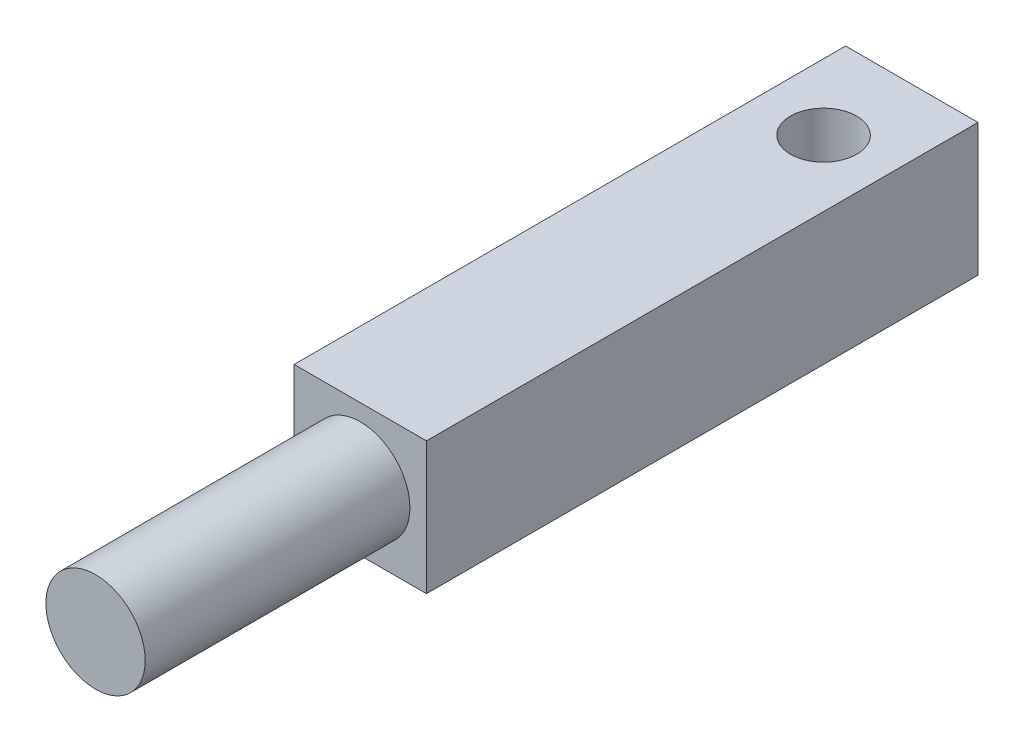
SolidWorks part; units mm, degrees
ref_plane "Alzado" through (0, 0, 0) normal (0, 0, 1) x (1, 0, 0)
ref_plane "Planta" through (0, 0, 0) normal (0, 1, 0) x (1, 0, 0)
ref_plane "Vista lateral" through (0, 0, 0) normal (1, 0, 0) x (0, 0, -1)
sketch "Croquis1" plane through (0, 0, 0) normal (0, 0, 1) x (1, 0, 0)
  line L1 (-6, -6) -> (6, -6)
  line L2 (-6, -6) -> (-6, 6)
  line L3 (-6, 6) -> (6, 6)
  line L4 (6, -6) -> (6, 6)
  line L5 (-6, -6) -> (6, 6) construction
  line L6 (-6, 6) -> (6, -6) construction
  point P0 (0, 0)
  dimension "D1" = 12
  dimension "D2" = 12
extrude "Saliente-Extruir1" add sketch "Croquis1" along normal blind 50
sketch "Croquis2" plane through (0, 0, 50) normal (0, 0, 1) x (1, 0, 0)
  line L0 (6, 6) -> (-6, -6) construction
  line L1 (-6, 6) -> (6, -6) construction
  circle A0 centre (0, 0) radius 4.5
  dimension "D1" = 9
extrude "Saliente-Extruir2" add sketch "Croquis2" along normal blind 24
sketch "Croquis3" plane through (0, 6, 0) normal (0, 1, 0) x (1, 0, 0)
  line L0 (-6, 0) -> (6, 0) construction
  line L2 (6, -50) -> (6, 0) construction
  circle A0 centre (0, -8) radius 3
  dimension "D2" = 6
  dimension "D4" = 6
  dimension "D1" = 12
  dimension "D3" = 8
extrude "Cortar-Extruir1" cut sketch "Croquis3" against normal through all
